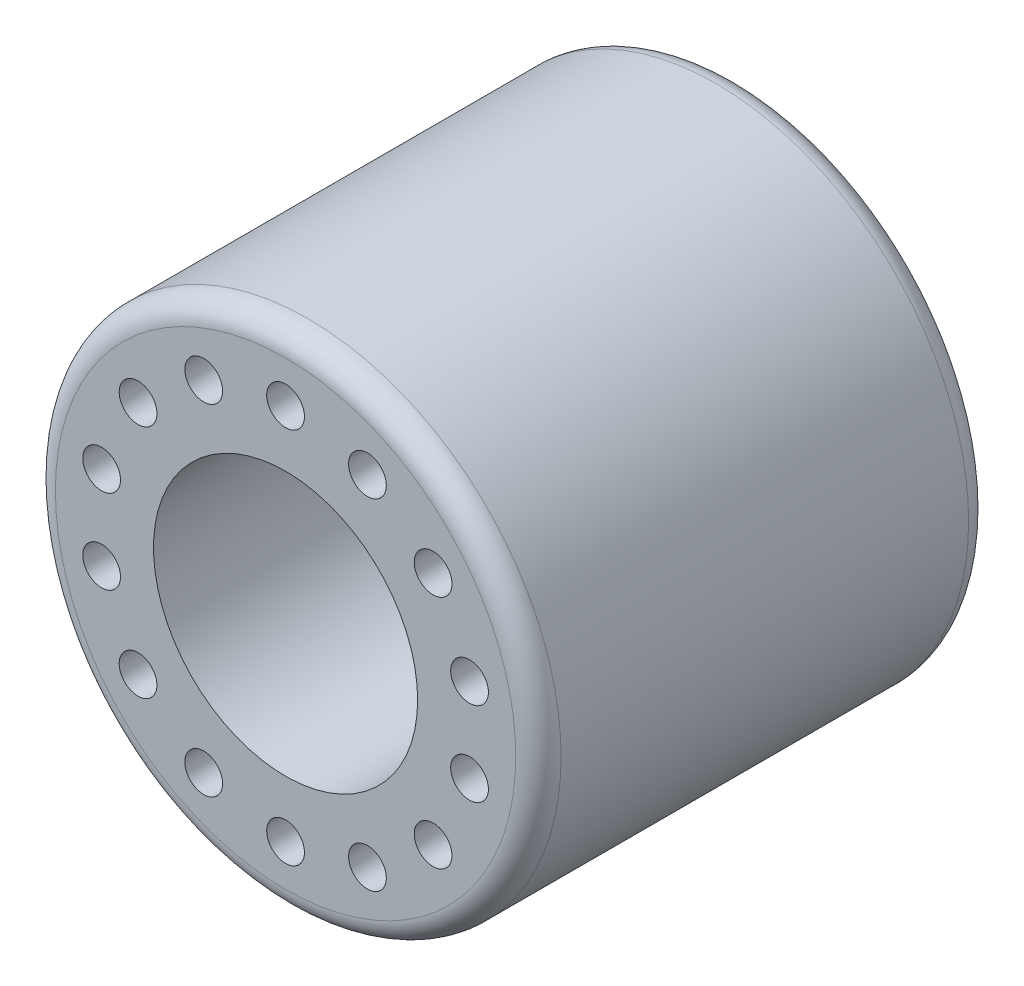
SolidWorks part; units mm, degrees
ref_plane "Front Plane" through (0, 0, 0) normal (0, 0, 1) x (1, 0, 0)
ref_plane "Top Plane" through (0, 0, 0) normal (0, 1, 0) x (1, 0, 0)
ref_plane "Right Plane" through (0, 0, 0) normal (1, 0, 0) x (0, 0, -1)
sketch "Sketch1" plane through (0, 0, 0) normal (0, 0, 1) x (1, 0, 0)
  circle A0 centre (0, 0) radius 4.445
  circle A1 centre (0, 0) radius 8.509
  dimension "D1" = 17.018
  dimension "D2" = 8.89
extrude "Boss-Extrude1" add sketch "Sketch1" along normal blind 15.24
fillet "Fillet1" radius 0.762 2 edges at (8.509, 0, 0) (8.509, 0, 15.24)
sketch "Sketch2" plane through (0, 0, 15.24) normal (0, 0, 1) x (1, 0, 0)
  circle A0 centre (0, 0) radius 6.35 construction
  circle A1 centre (0, 6.35) radius 0.635
  circle A2 centre (2.7552, 5.7212) radius 0.635
  circle A3 centre (4.9646, 3.9592) radius 0.635
  circle A4 centre (6.1908, 1.413) radius 0.635
  circle A5 centre (6.1908, -1.413) radius 0.635
  circle A6 centre (4.9646, -3.9592) radius 0.635
  circle A7 centre (2.7552, -5.7212) radius 0.635
  circle A8 centre (0, -6.35) radius 0.635
  circle A9 centre (-2.7552, -5.7212) radius 0.635
  circle A10 centre (-4.9646, -3.9592) radius 0.635
  circle A11 centre (-6.1908, -1.413) radius 0.635
  circle A12 centre (-6.1908, 1.413) radius 0.635
  circle A13 centre (-4.9646, 3.9592) radius 0.635
  circle A14 centre (-2.7552, 5.7212) radius 0.635
  point P34 (0, 0)
  dimension "D1" = 12.7
  dimension "D2" = 1.27
  dimension "D3" = 14
extrude "Cut-Extrude1" cut sketch "Sketch2" against normal blind 1.27
